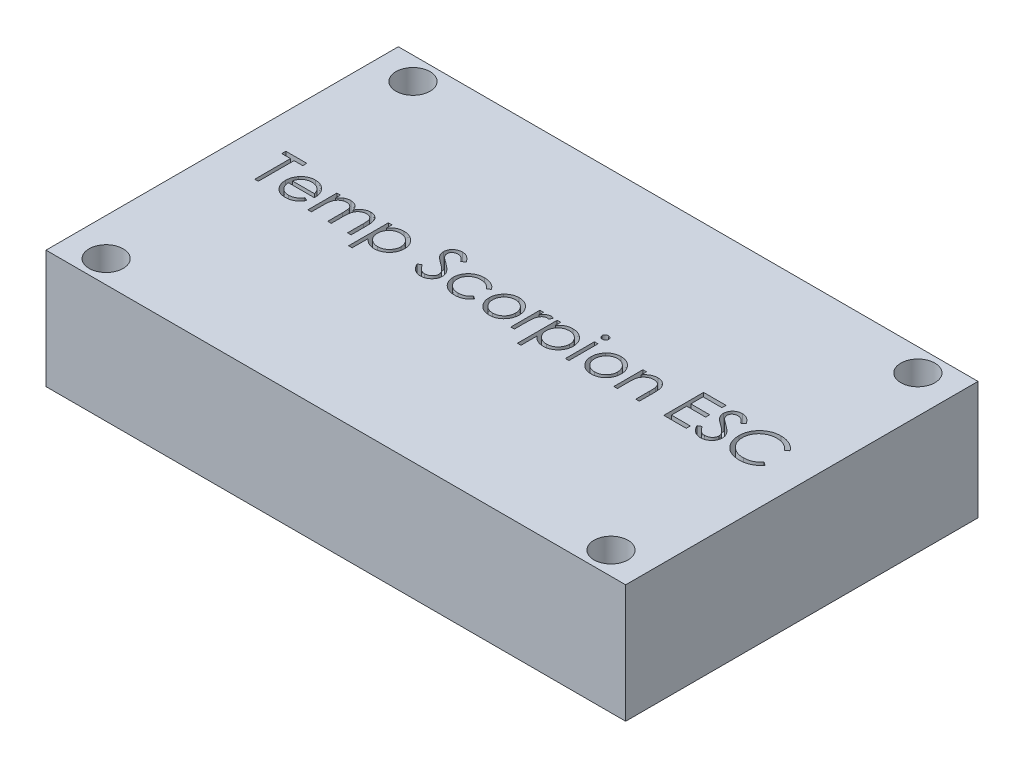
SolidWorks part; units mm, degrees
ref_plane "Front Plane" through (0, 0, 0) normal (0, 0, 1) x (1, 0, 0)
ref_plane "Top Plane" through (0, 0, 0) normal (0, 1, 0) x (1, 0, 0)
ref_plane "Right Plane" through (0, 0, 0) normal (1, 0, 0) x (0, 0, -1)
sketch "Sketch1" plane through (0, 0, 0) normal (0, 1, 0) x (1, 0, 0)
  line L0 (-22.2097, 13.5) -> (22.2097, 13.5) construction
  line L1 (-25.5, -15.5) -> (25.5, -15.5)
  line L2 (-25.5, -15.5) -> (-25.5, 15.5)
  line L3 (-25.5, 15.5) -> (25.5, 15.5)
  line L4 (25.5, -15.5) -> (25.5, 15.5)
  line L5 (-25.5, -15.5) -> (25.5, 15.5) construction
  line L6 (-25.5, 15.5) -> (25.5, -15.5) construction
  line L7 (22.2097, 13.5) -> (22.2097, -13.5) construction
  line L8 (22.2097, -13.5) -> (-22.2097, -13.5) construction
  line L9 (-22.2097, -13.5) -> (-22.2097, 13.5) construction
  circle A0 centre (-22.2097, -13.5) radius 1.5
  circle A1 centre (-22.2097, 13.5) radius 1.5
  circle A2 centre (22.2097, 13.5) radius 1.5
  circle A3 centre (22.2097, -13.5) radius 1.5
  point P0 (0, 0)
  dimension "D3" = 3
  dimension "D4" = 3
  dimension "D5" = 3
  dimension "D6" = 3
  dimension "D1" = 51
  dimension "D2" = 31
  dimension "D7" = 2
  dimension "D8" = 2
  dimension "D9" = 2
  dimension "D10" = 2
  dimension "D11" = 44.4194
  dimension "D12" = 27
  dimension "D13" = 2
extrude "Boss-Extrude1" add sketch "Sketch1" along normal blind 10.4
sketch "Sketch2" plane through (0, 10.4, 0) normal (0, 1, 0) x (1, 0, 0)
  text T0 "Temp Scorpion ESC"
extrude "Cut-Extrude1" cut sketch "Sketch2" against normal blind 1.4
